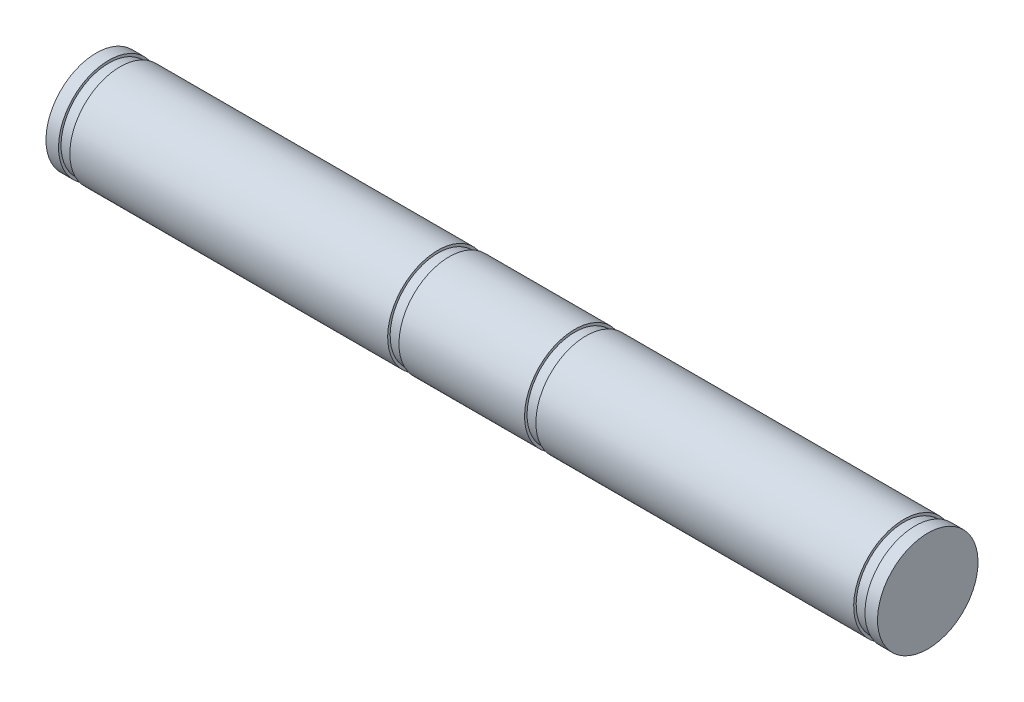
SolidWorks part; units mm, degrees
material "Plain Carbon Steel"
ref_plane "Front Plane" through (0, 0, 0) normal (0, 0, 1) x (1, 0, 0)
ref_plane "Top Plane" through (0, 0, 0) normal (0, 1, 0) x (1, 0, 0)
ref_plane "Right Plane" through (0, 0, 0) normal (1, 0, 0) x (0, 0, -1)
sketch "Sketch1" plane through (0, 0, 0) normal (0, 0, 1) x (1, 0, 0)
  line L0 (0, 0) -> (64.3, 0)
  line L1 (64.3, 0) -> (64.3, 4)
  line L2 (64.3, 4) -> (63.3, 4)
  line L3 (63.3, 4) -> (63.3, 3.8)
  line L4 (63.3, 3.8) -> (62.4, 3.8)
  line L5 (62.4, 3.8) -> (62.4, 4)
  line L6 (62.4, 4) -> (37.1, 4)
  line L7 (0, 4) -> (0, 3.8)
  line L8 (31.2, 4) -> (31.2, 0) construction
  line L9 (0, 3.8) -> (0, 4)
  line L10 (-0.9, 3.8) -> (0, 3.8)
  line L11 (-0.9, 4) -> (-0.9, 3.8)
  line L12 (-1.9, 4) -> (-0.9, 4)
  line L13 (-1.9, 0) -> (-1.9, 4)
  line L14 (-1.9, 0) -> (0, 0)
  line L15 (37.1, 4) -> (37.1, 3.8)
  line L16 (37.1, 3.8) -> (36.2, 3.8)
  line L17 (36.2, 3.8) -> (36.2, 4)
  line L18 (36.2, 4) -> (26.2, 4)
  line L19 (26.2, 3.8) -> (26.2, 4)
  line L20 (25.3, 3.8) -> (26.2, 3.8)
  line L21 (25.3, 4) -> (25.3, 3.8)
  line L22 (25.3, 4) -> (0, 4)
  point P18 (36.2, 3.9)
  dimension "D1" = 62.4
  dimension "D2" = 0.9
  dimension "D3" = 4
  dimension "D4" = 1
  dimension "D5" = 4
  dimension "D6" = 3.8
  dimension "D7" = 3.8
  dimension "D8" = 0.9
  dimension "D9" = 26.2
revolve "Revolve1" add sketch "Sketch1" angle 360 about L0
